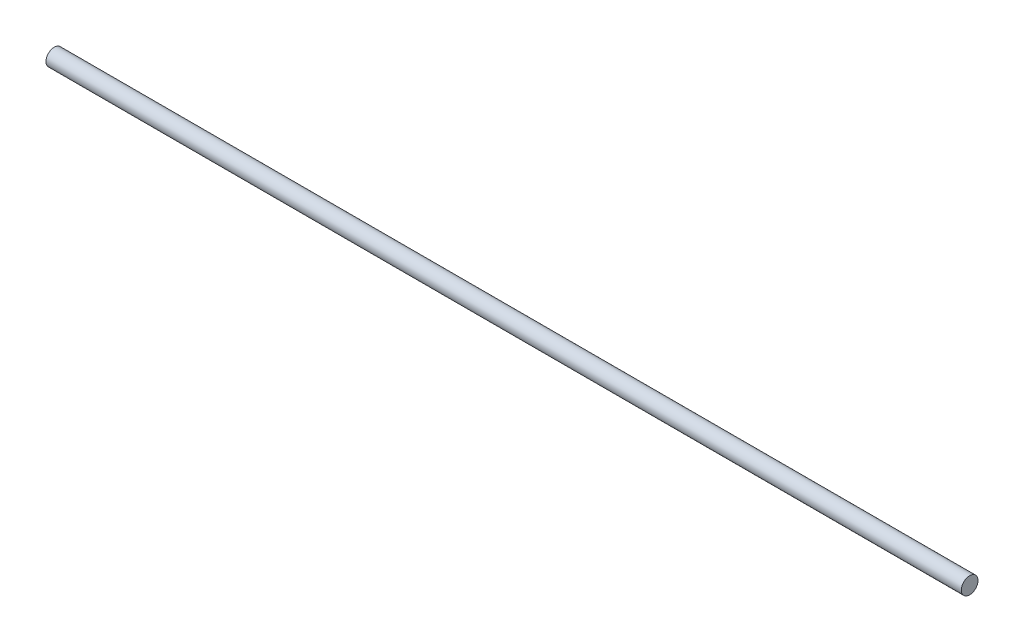
SolidWorks part; units mm, degrees
ref_plane "前视基准面" through (0, 0, 0) normal (0, 0, 1) x (1, 0, 0)
ref_plane "上视基准面" through (0, 0, 0) normal (0, 1, 0) x (1, 0, 0)
ref_plane "右视基准面" through (0, 0, 0) normal (1, 0, 0) x (0, 0, -1)
sketch "草图1" plane through (0, 0, 0) normal (1, 0, 0) x (0, 0, -1)
  circle A0 centre (0, 0) radius 2
  dimension "D1" = 4
extrude "凸台-拉伸1" add sketch "草图1" along normal mid plane 220
